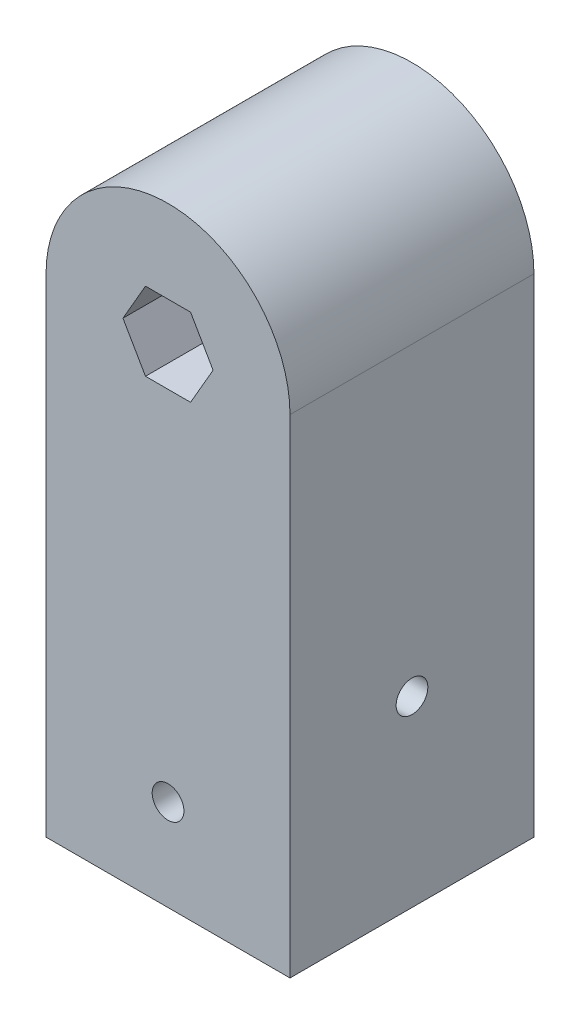
SolidWorks part; units mm, degrees
ref_plane "Front Plane" through (0, 0, 0) normal (0, 0, 1) x (1, 0, 0)
ref_plane "Top Plane" through (0, 0, 0) normal (0, 1, 0) x (1, 0, 0)
ref_plane "Right Plane" through (0, 0, 0) normal (1, 0, 0) x (0, 0, -1)
sketch "Sketch2" plane through (0, 0, 0) normal (0, 0, 1) x (1, 0, 0)
  line L0 (-10, 0) -> (-10, -40)
  line L1 (3.695, 0) -> (1.8475, 3.2)
  line L2 (1.8475, 3.2) -> (-1.8475, 3.2)
  line L3 (-1.8475, 3.2) -> (-3.695, 0)
  line L4 (-3.695, 0) -> (-1.8475, -3.2)
  line L5 (-1.8475, -3.2) -> (1.8475, -3.2)
  line L6 (1.8475, -3.2) -> (3.695, 0)
  line L7 (-10, -40) -> (10, -40)
  line L8 (10, -40) -> (10, 0)
  circle A0 centre (0, 0) radius 3.2 construction
  arc A1 (10, 0) -> (-10, 0) centre (0, 0) ccw
  arc A2 (-10, 0) -> (10, 0) centre (0, 0) ccw construction
  dimension "D2" = 20
  dimension "D1" = 6.4
  dimension "D3" = 40
extrude "Boss-Extrude1" add sketch "Sketch2" along normal mid plane 20
sketch "Sketch3" plane through (0, -40, 0) normal (0, -1, 0) x (1, 0, 0)
  line L2 (10, 10) -> (10, -10) construction
  circle A0 centre (0, 0) radius 4.9
  point P2 (0, 0)
  point P3 (0, 0)
  point P7 (10, 0)
  dimension "D1" = 9.8
extrude "Cut-Extrude1" cut sketch "Sketch3" against normal blind 20
sketch "Sketch4" plane through (0, 0, 0) normal (0, 0, 1) x (1, 0, 0)
  line L0 (-10, -40) -> (10, -40) construction
  circle A0 centre (0, -32.5) radius 1.3
  point P4 (0, 0)
  dimension "D2" = 2.6
  dimension "D1" = 7.5
extrude "Cut-Extrude2" cut sketch "Sketch4" against normal through all both and the other way through all
sketch "Sketch5" plane through (0, 0, 0) normal (1, 0, 0) x (0, 0, -1)
  line L0 (-10, -40) -> (10, -40) construction
  circle A0 centre (0, -25) radius 1.3
  point P4 (0, 0)
  point P5 (0, -40)
  dimension "D2" = 2.6
  dimension "D1" = 15
extrude "Cut-Extrude3" cut sketch "Sketch5" against normal through all both and the other way through all
